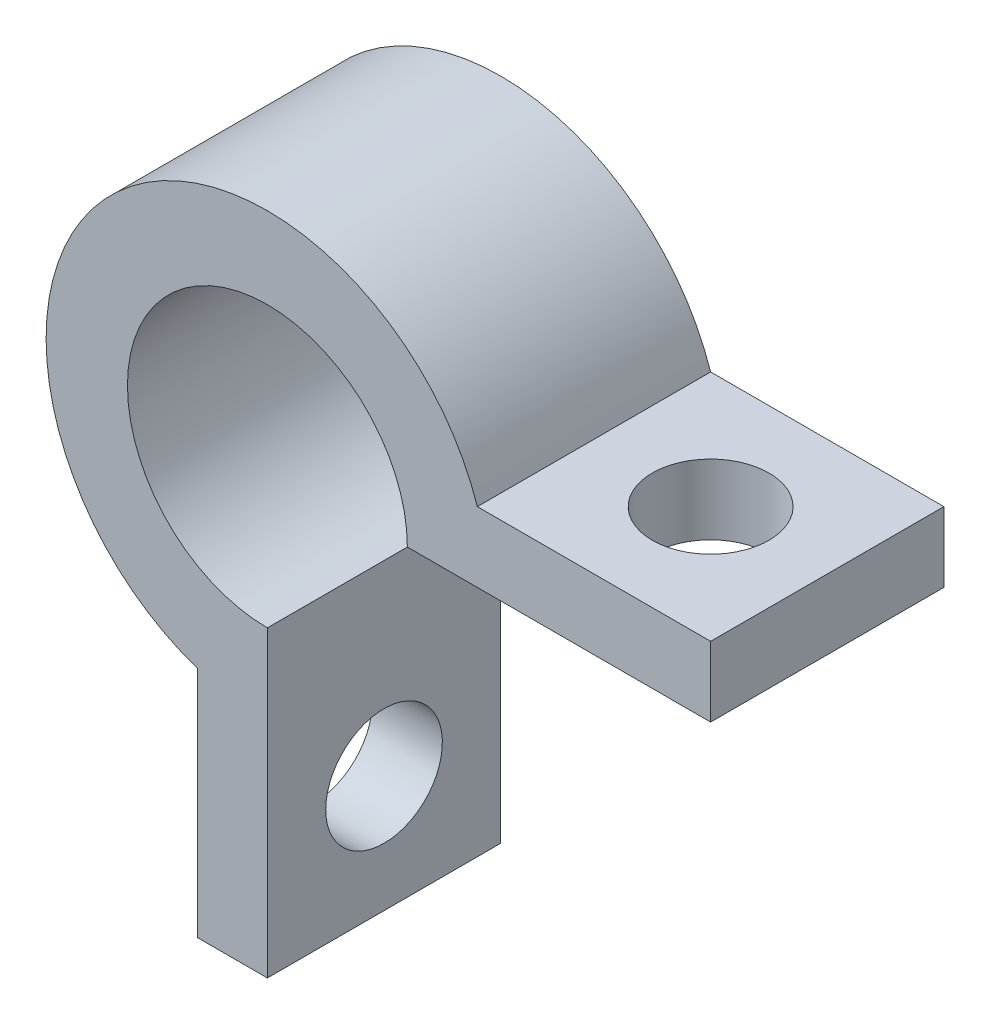
SolidWorks part; units mm, degrees
ref_plane "Front Plane" through (0, 0, 0) normal (0, 0, 1) x (1, 0, 0)
ref_plane "Top Plane" through (0, 0, 0) normal (0, 1, 0) x (1, 0, 0)
ref_plane "Right Plane" through (0, 0, 0) normal (1, 0, 0) x (0, 0, -1)
sketch "Sketch1" plane through (0, 0, 0) normal (0, 0, 1) x (1, 0, 0)
  line L0 (-3.81, -3.81) -> (-3.81, -16.51)
  line L1 (-3.81, -16.51) -> (0, -16.51)
  line L2 (0, -16.51) -> (0, 0)
  line L3 (7.62, 7.62) -> (24.13, 7.62)
  line L4 (24.13, 7.62) -> (24.13, 11.43)
  line L5 (24.13, 11.43) -> (11.43, 11.43)
  arc A0 (0, 0) -> (7.62, 7.62) centre (0, 7.62) cw
  arc A1 (-3.81, -3.81) -> (11.43, 11.43) centre (0, 7.62) cw
  point P5 (6.0489, 12.151)
  point P8 (11.0919, 6.5589)
  point P12 (-4.8818, -11.4406)
  point P13 (12.5864, 6.5257)
  point P14 (8.1031, 6.0275)
  point P15 (7.5385, 2.1752)
  point P16 (4.4579, 6.1799)
  point P17 (11.026, 11.3208)
  point P18 (2.3637, 7.2441)
  point P19 (0, 0)
  dimension "D2" = 7.62
  dimension "D1" = 3.81
  dimension "D3" = 12.7
  dimension "D4" = 3.81
extrude "Boss-Extrude1" add sketch "Sketch1" along normal blind 12.7
sketch "Sketch2" plane through (0, 11.43, 0) normal (0, 1, 0) x (1, 0, 0)
  line L0 (17.78, 0) -> (17.78, -12.7) construction
  line L1 (24.13, 0) -> (11.43, 0) construction
  line L2 (24.13, -12.7) -> (11.43, -12.7) construction
  circle A0 centre (17.78, -6.35) radius 3.175
  dimension "D1" = 6.35
extrude "Cut-Extrude1" cut sketch "Sketch2" against normal through all
sketch "Sketch3" plane through (-3.81, 0, 0) normal (-1, 0, 0) x (0, 0, 1)
  line L0 (0, -10.16) -> (12.7, -10.16) construction
  line L1 (0, -3.81) -> (0, -16.51) construction
  line L2 (12.7, -3.81) -> (12.7, -16.51) construction
  circle A0 centre (6.35, -10.16) radius 3.175
  point P8 (6.35, -10.16)
  dimension "D1" = 6.35
extrude "Cut-Extrude2" cut sketch "Sketch3" against normal through all
